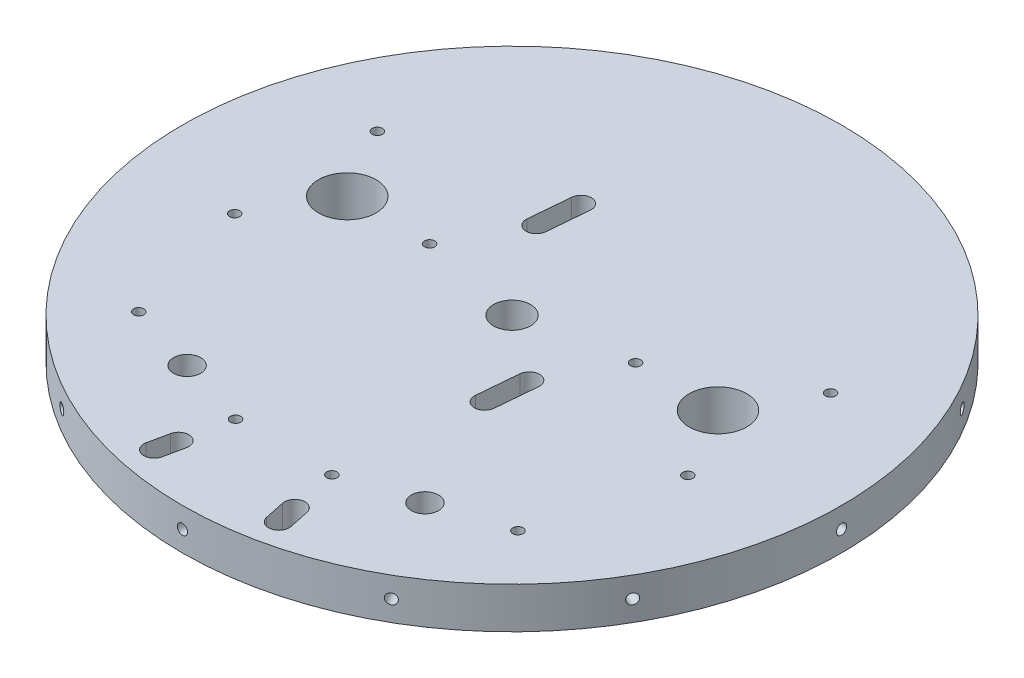
SolidWorks part; units mm, degrees
material "6061 Alloy"
ref_plane "Front Plane" through (0, 0, 0) normal (0, 0, 1) x (1, 0, 0)
ref_plane "Top Plane" through (0, 0, 0) normal (0, 1, 0) x (1, 0, 0)
ref_plane "Right Plane" through (0, 0, 0) normal (1, 0, 0) x (0, 0, -1)
sketch "Sketch1" plane through (0, 0, 0) normal (0, 1, 0) x (1, 0, 0)
  circle A0 centre (0, 0) radius 80
extrude "Boss-Extrude1" add sketch "Sketch1" against normal blind 10
sketch "Sketch3" plane through (0, 0, 0) normal (0, 1, 0) x (1, 0, 0)
  circle A0 centre (0, 0) radius 4.5
extrude "Cut-Extrude1" cut sketch "Sketch3" against normal blind 12
sketch "Sketch4" plane through (0, 0, 0) normal (0, 1, 0) x (1, 0, 0)
  line L1 (45, 5) -> (-45, 5)
  circle A2 centre (-45, 5) radius 7
  circle A3 centre (45, 5) radius 7
  point P5 (0, 0)
extrude "Cut-Extrude2" cut sketch "Sketch4" against normal blind 12
ref_plane "Plane1" through (0, 0, 80) normal (0, 0, 1) x (1, 0, 0)
sketch "Sketch5" plane through (0, 0, 80) normal (0, 0, 1) x (1, 0, 0)
  line L0 (80, 0) -> (-80, 0) construction
  circle A0 centre (0, -5) radius 1.25
  dimension "D1" = 5
extrude "Cut-Extrude3" cut sketch "Sketch5" against normal blind 15
pattern_circular "CirPattern1" count 12 over 360 about axis through (0, 0, 0) along (0, 1, 0) of "Cut-Extrude3"
sketch "Sketch6" plane through (0, 0, 0) normal (0, 1, 0) x (1, 0, 0)
  line L2 (-45, 5) -> (-25, 5) construction
  line L3 (45, 5) -> (25, 5) construction
  circle A2 centre (-25, 5) radius 1.25
  circle A3 centre (25, 5) radius 1.25
  circle A4 centre (-55, 22.3205) radius 1.25
  circle A5 centre (-55, -12.3205) radius 1.25
  circle A6 centre (55, 22.3205) radius 1.25
  circle A7 centre (55, -12.3205) radius 1.25
  point P7 (-45, 5)
  point P18 (45, 5)
  dimension "D1" = 3
  dimension "D2" = 3
extrude "Cut-Extrude4" cut sketch "Sketch6" against normal up to next
sketch "Sketch9" plane through (0, -10, 0) normal (0, -1, 0) x (1, 0, 0)
  circle A0 centre (0, 0) radius 12.5
extrude "Cut-Extrude5" cut sketch "Sketch9" against normal blind 3
sketch "Sketch10" plane through (0, 0, 0) normal (0, 1, 0) x (1, 0, 0)
  line L0 (0, 0) -> (0, -80) construction
  line L1 (0, 0) -> (28.8675, -50)
  line L2 (0, 0) -> (-28.8675, -50)
  line L4 (-28.8675, -50) -> (28.8675, -50)
  circle A0 centre (0, 0) radius 80 construction
  circle A4 centre (-28.8675, -50) radius 3.3
  circle A5 centre (28.8675, -50) radius 3.3
  point P12 (17.3205, -60)
  dimension "D1" = 30
  dimension "D2" = 30
extrude "Cut-Extrude6" cut sketch "Sketch10" against normal up to next contours L1 A5 L4 | L4 A5 L1 | A4
sketch "Sketch11" plane through (0, 0, 0) normal (0, 1, 0) x (1, 0, 0)
  line L0 (0, 0) -> (0, -80) construction
  line L1 (28.8675, -50) -> (0, -59.1019) construction
  line L2 (0, -59.1019) -> (-28.8675, -50) construction
  circle A0 centre (0, 0) radius 80 construction
  circle A1 centre (11.7006, -55.4127) radius 1.25
  circle A2 centre (-11.7006, -55.4127) radius 1.25
  circle A3 centre (46.0344, -44.5873) radius 1.25
  circle A4 centre (-46.0344, -44.5873) radius 1.25
  point P20 (28.8675, -50)
  point P22 (-28.8675, -50)
  dimension "D2" = 18
  dimension "D3" = 18
  dimension "D1" = 145
  dimension "D4" = 2
  dimension "D5" = 2
extrude "Cut-Extrude7" cut sketch "Sketch11" against normal up to next
sketch "Sketch12" plane through (0, 0, 0) normal (0, 1, 0) x (1, 0, 0)
  line L0 (0, 0) -> (16.5279, -78.2741) construction
  line L1 (0, 0) -> (-16.5279, -78.2741) construction
  line L4 (16.5603, -66.3269) -> (17.5933, -71.219)
  line L5 (12.7012, -72.252) -> (11.6682, -67.3599)
  line L6 (-11.6682, -67.3599) -> (-12.7012, -72.252)
  line L7 (-16.5603, -66.3269) -> (-17.5933, -71.219)
  arc A1 (16.5603, -66.3269) -> (11.6682, -67.3599) centre (14.1142, -66.8434) ccw
  arc A2 (-11.6682, -67.3599) -> (-16.5603, -66.3269) centre (-14.1142, -66.8434) ccw
  arc A3 (-17.5933, -71.219) -> (-12.7012, -72.252) centre (-15.1472, -71.7355) ccw
  arc A4 (12.7012, -72.252) -> (17.5933, -71.219) centre (15.1472, -71.7355) ccw
  circle A5 centre (0, 0) radius 80 construction
  dimension "D1" = 5
  dimension "D2" = 5
extrude "Cut-Extrude8" cut sketch "Sketch12" against normal up to next
sketch "Sketch13" plane through (0, 0, 0) normal (0, 1, 0) x (1, 0, 0)
  line L0 (28.8675, -50) -> (0, 0) construction
  line L1 (0, 0) -> (-40, 69.282) construction
  line L2 (33.1976, -47.5) -> (4.3301, 2.5) construction
  line L3 (18.0385, -14.28) -> (17.6027, -19.2609)
  line L4 (13.0575, -13.8442) -> (12.6218, -18.8252)
  line L5 (-17.8099, 0.4442) -> (-13.1901, 53.2494) construction
  line L6 (9.2515, -86.0316) -> (21.4088, 52.9265) construction
  line L7 (-12.7916, 29.1194) -> (-13.2274, 24.1384)
  line L8 (-17.7726, 29.5552) -> (-18.2084, 24.5742)
  line L9 (-12.5737, 31.6099) -> (-13.4453, 21.6479)
  line L10 (-17.5547, 32.0457) -> (-18.4263, 22.0837)
  line L11 (18.2564, -11.7895) -> (17.3848, -21.7514)
  line L12 (13.2754, -11.3537) -> (12.4039, -21.3156)
  circle A0 centre (0, 0) radius 80 construction
  arc A11 (-12.5737, 31.6099) -> (-17.5547, 32.0457) centre (-15.0642, 31.8278) ccw
  arc A12 (-18.4263, 22.0837) -> (-13.4453, 21.6479) centre (-15.9358, 21.8658) ccw
  arc A14 (18.2564, -11.7895) -> (13.2754, -11.3537) centre (15.7659, -11.5716) ccw
  arc A15 (-13.4521, 23.2998) -> (-13.2274, 24.1384) centre (-15.7179, 24.3563) ccw
  arc A16 (12.4039, -21.3156) -> (17.3848, -21.7514) centre (14.8943, -21.5335) ccw
  point P16 (-15.5, 26.8468)
  point P19 (15.3301, -16.5526)
  point P22 (-15.5, 26.8468)
  point P25 (15.3301, -16.5526)
  point P26 (15.3301, -16.5526)
  dimension "D2" = 35
  dimension "D3" = 35
  dimension "D1" = 5
extrude "Cut-Extrude10" cut sketch "Sketch13" against normal up to next
